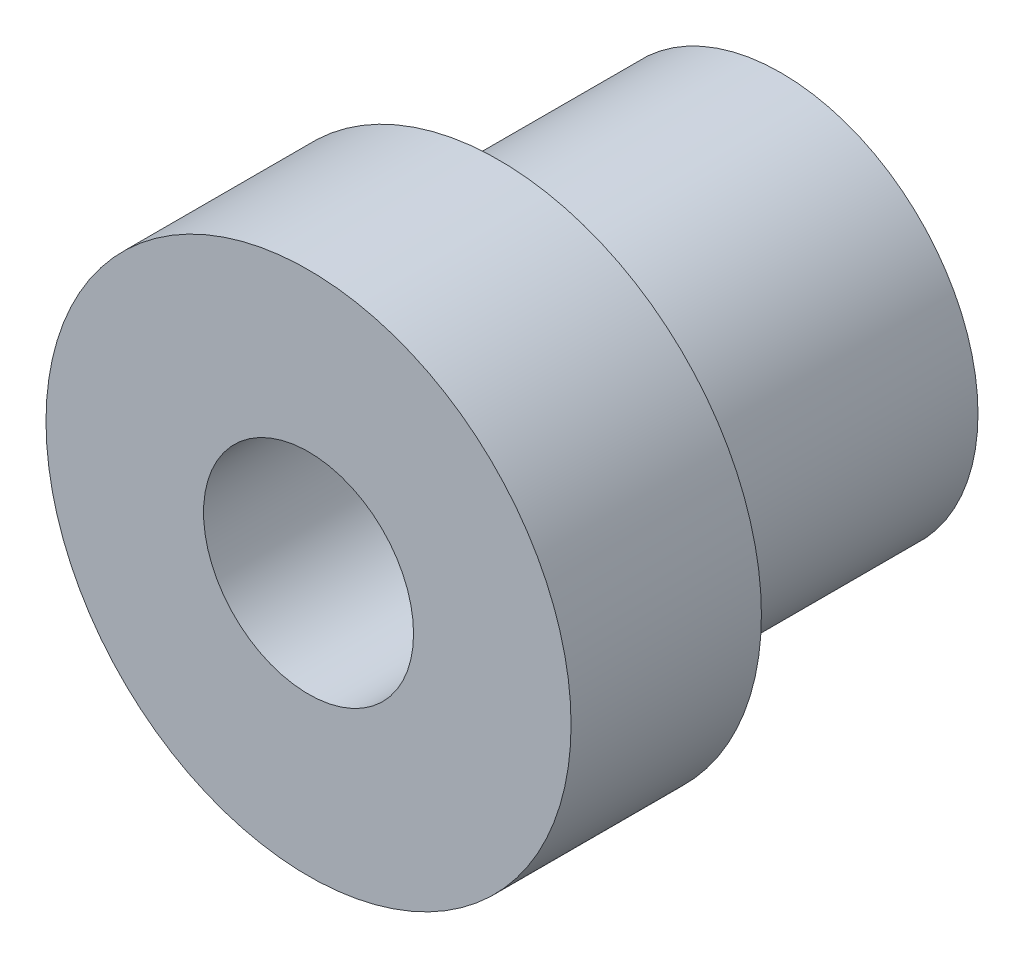
SolidWorks part; units mm, degrees
ref_plane "前视基准面" through (0, 0, 0) normal (0, 0, 1) x (1, 0, 0)
ref_plane "上视基准面" through (0, 0, 0) normal (0, 1, 0) x (1, 0, 0)
ref_plane "右视基准面" through (0, 0, 0) normal (1, 0, 0) x (0, 0, -1)
sketch "草图1" plane through (0, 0, 0) normal (0, 0, 1) x (1, 0, 0)
  circle A0 centre (0, 0) radius 4
  dimension "D1" = 8
extrude "凸台-拉伸1" add sketch "草图1" along normal blind 7
sketch "草图2" plane through (0, 0, 7) normal (0, 0, 1) x (1, 0, 0)
  circle A0 centre (0, 0) radius 1.6
  dimension "D1" = 3.2
extrude "切除-拉伸1" cut sketch "草图2" against normal through all
sketch "草图3" plane through (0, 0, 7) normal (0, 0, 1) x (1, 0, 0)
  circle A0 centre (0, 0) radius 3
  dimension "D1" = 6
extrude "切除-拉伸2" cut sketch "草图3" against normal blind 4 flip side to cut
sketch "草图4" plane through (0, 0, 7) normal (0, 0, 1) x (1, 0, 0)
  circle A0 centre (0, 0) radius 1.6 construction
  circle A1 centre (0, 0) radius 4
  circle A2 centre (0, 0) radius 4
  circle A3 centre (0, 0) radius 1.6
  dimension "D1" = 0
extrude "凸台-拉伸2" add sketch "草图4" along normal blind 3
ref_plane "基准面1" through (0, 0, 5) normal (0, 0, 1) x (1, 0, 0)
sketch "草图5" plane through (0, 0, 5) normal (0, 0, 1) x (1, 0, 0)
  circle A0 centre (0, 0) radius 4 construction
  circle A1 centre (0, 0) radius 3 construction
  circle A2 centre (0, 0) radius 4
  circle A3 centre (0, 0) radius 3
extrude "切除-拉伸3" cut sketch "草图5" against normal mid plane 4.2
sketch "草图6" plane through (0, 0, 0) normal (0, 0, -1) x (-1, 0, 0)
  circle A0 centre (0, 0) radius 3 construction
  circle A1 centre (0, 0) radius 3
extrude "切除-拉伸4" cut sketch "草图6" against normal blind 7 flip side to cut
sketch "草图7" plane through (0, 0, 0) normal (0, 0, -1) x (-1, 0, 0)
  circle A0 centre (0, 0) radius 3
extrude "切除-拉伸5" cut sketch "草图7" against normal blind 2.8
